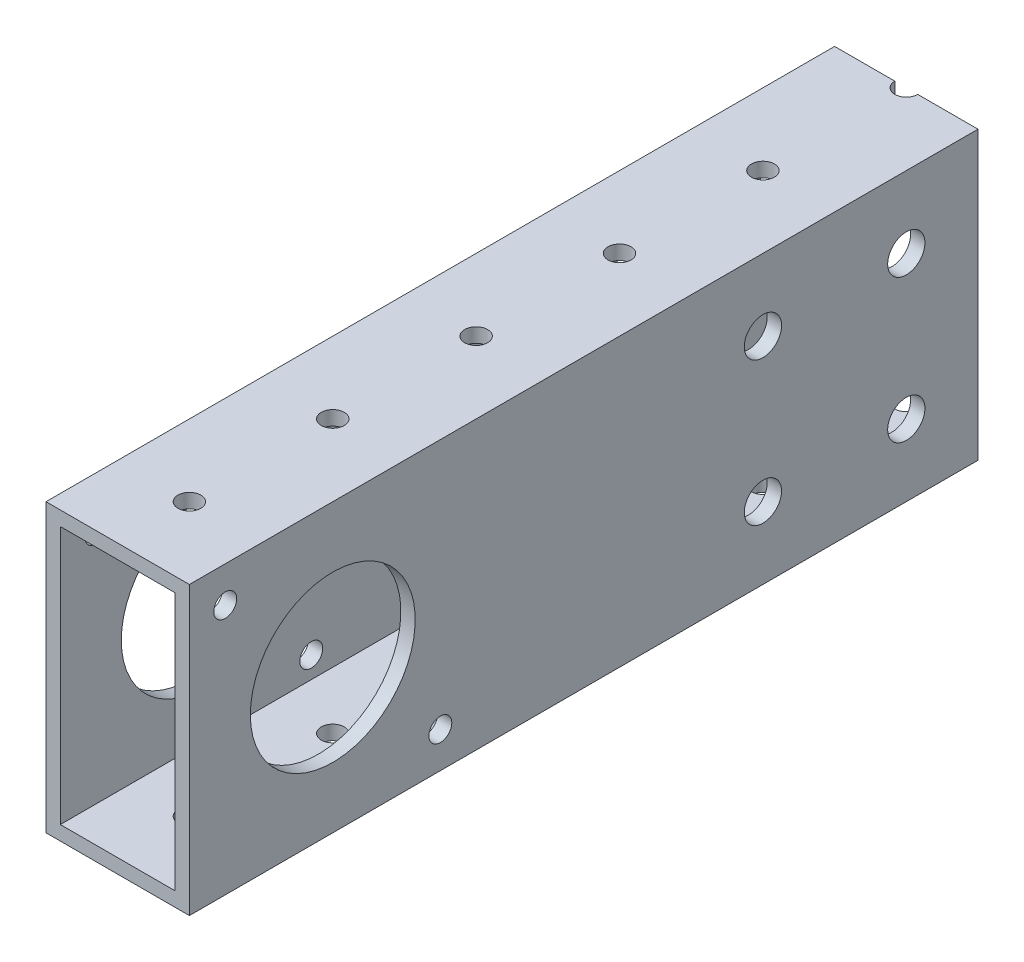
SolidWorks part; units mm, degrees
ref_plane "Front Plane" through (0, 0, 0) normal (0, 0, 1) x (1, 0, 0)
ref_plane "Top Plane" through (0, 0, 0) normal (0, 1, 0) x (1, 0, 0)
ref_plane "Right Plane" through (0, 0, 0) normal (1, 0, 0) x (0, 0, -1)
sketch "Sketch1" plane through (0, 0, 0) normal (0, 0, 1) x (1, 0, 0)
  line L0 (-10.16, 22.86) -> (10.16, 22.86)
  line L1 (-12.7, -25.4) -> (12.7, -25.4)
  line L2 (-12.7, -25.4) -> (-12.7, 25.4)
  line L3 (-12.7, 25.4) -> (12.7, 25.4)
  line L4 (12.7, -25.4) -> (12.7, 25.4)
  line L5 (-12.7, -25.4) -> (12.7, 25.4) construction
  line L6 (-12.7, 25.4) -> (12.7, -25.4) construction
  line L7 (10.16, -22.86) -> (10.16, 22.86)
  line L8 (-10.16, -22.86) -> (10.16, -22.86)
  line L9 (-10.16, -22.86) -> (-10.16, 22.86)
  point P0 (0, 0)
  dimension "D1" = 25.4
  dimension "D2" = 50.8
  dimension "D3" = 2.54
extrude "Boss-Extrude1" add sketch "Sketch1" along normal blind 139.7
sketch "Sketch2" plane through (0, 25.4, 0) normal (0, 1, 0) x (1, 0, 0)
  line L0 (12.7, 0) -> (-12.7, 0) construction
  circle A0 centre (0, 0) radius 2.032
  circle A1 centre (0, -25.4) radius 2.032
  circle A2 centre (0, -50.8) radius 2.032
  circle A3 centre (0, -76.2) radius 2.032
  circle A4 centre (0, -101.6) radius 2.032
  circle A5 centre (0, -127) radius 2.032
  circle A6 centre (0, -152.4) radius 2.032
  circle A7 centre (0, -177.8) radius 2.032
  circle A8 centre (0, -203.2) radius 2.032
  circle A9 centre (0, -228.6) radius 2.032
  dimension "D1" = 4.064
  dimension "D2" = 10
extrude "Cut-Extrude1" cut sketch "Sketch2" against normal through all
sketch "Sketch3" plane through (-12.7, 0, 0) normal (-1, 0, 0) x (0, 0, 1)
  line L0 (139.7, 25.4) -> (139.7, -25.4) construction
  line L1 (139.7, 25.4) -> (0, 25.4) construction
  line L2 (139.7, -25.4) -> (0, -25.4) construction
  line L3 (99.695, 0) -> (128.905, 0) construction
  line L4 (12.7, 12.7) -> (38.1, 12.7) construction
  line L5 (0, 25.4) -> (0, -25.4) construction
  line L6 (12.7, -12.7) -> (38.1, -12.7) construction
  circle A0 centre (133.35, 19.05) radius 2.032
  circle A1 centre (95.25, -19.05) radius 2.032
  circle A2 centre (114.3, 0) radius 14.605
  circle A3 centre (12.7, 12.7) radius 3.302
  circle A4 centre (38.1, 12.7) radius 3.302
  circle A5 centre (38.1, -12.7) radius 3.302
  circle A6 centre (12.7, -12.7) radius 3.302
  point P8 (139.7, 0)
  dimension "D1" = 4.064
  dimension "D6" = 29.21
  dimension "D9" = 6.604
  dimension "D2" = 6.35
  dimension "D3" = 6.35
  dimension "D4" = 44.45
  dimension "D5" = 6.35
  dimension "D7" = 25.4
  dimension "D8" = 25.4
  dimension "D10" = 25.4
  dimension "D11" = 12.7
  dimension "D12" = 12.7
extrude "Cut-Extrude2" cut sketch "Sketch3" against normal through all
